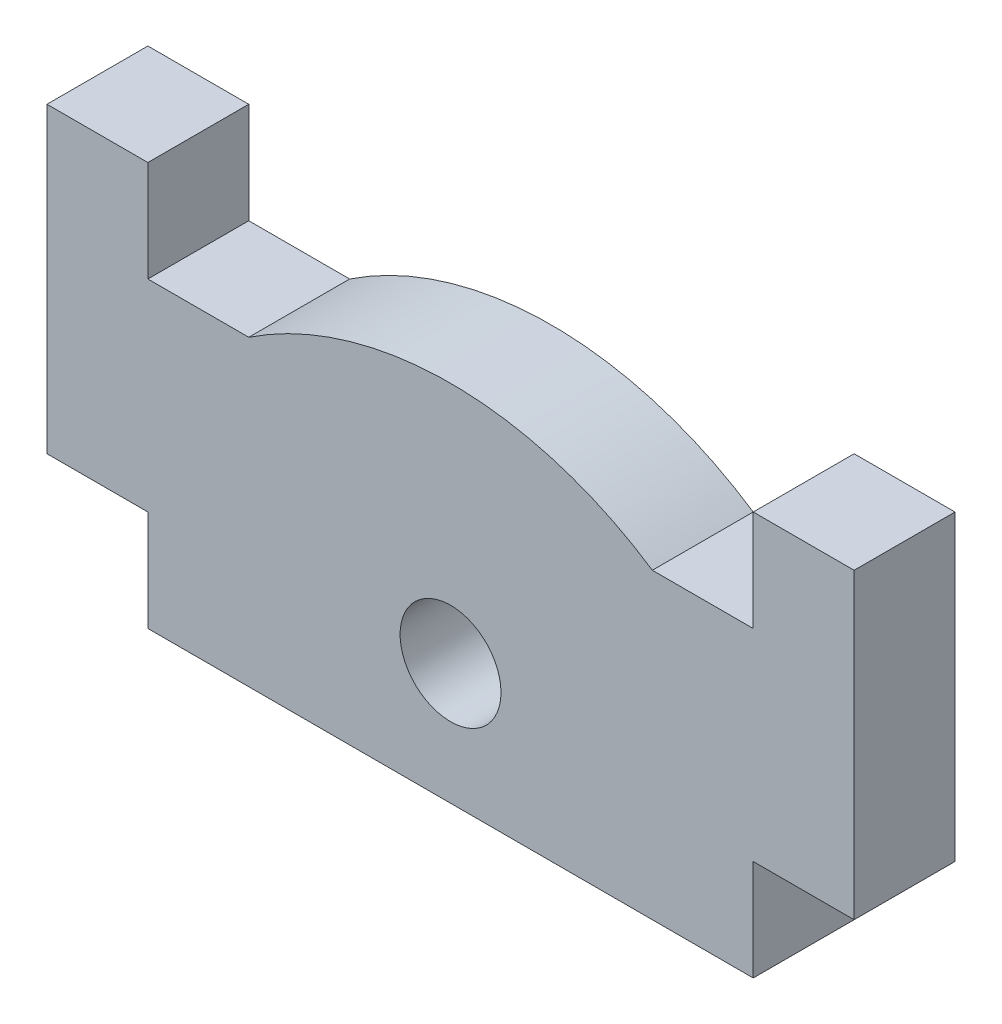
SolidWorks part; units mm, degrees
ref_plane "Front Plane" through (0, 0, 0) normal (0, 0, 1) x (1, 0, 0)
ref_plane "Top Plane" through (0, 0, 0) normal (0, 1, 0) x (1, 0, 0)
ref_plane "Right Plane" through (0, 0, 0) normal (1, 0, 0) x (0, 0, -1)
sketch "Sketch1" plane through (0, 0, 0) normal (0, 0, 1) x (1, 0, 0)
  line L0 (0, 0) -> (0, 14.5454) construction
  line L1 (0, 0) -> (18.3347, 0) construction
  line L2 (0, 6) -> (4, 6) construction
  line L3 (4, 6) -> (6, 6)
  line L4 (6, 6) -> (6, 8)
  line L5 (6, 8) -> (8, 8)
  line L6 (8, 8) -> (8, 2)
  line L7 (8, 2) -> (6, 2)
  line L8 (6, 2) -> (6, 0)
  line L9 (6, 0) -> (-6, 0)
  line L10 (-6, 2) -> (-6, 0)
  line L11 (-4, 6) -> (-6, 6)
  line L12 (-8, 2) -> (-6, 2)
  line L13 (-8, 8) -> (-8, 2)
  line L14 (-6, 8) -> (-8, 8)
  line L15 (-6, 6) -> (-6, 8)
  arc A0 (4, 6) -> (-4, 6) centre (0, 0) ccw
  circle A1 centre (0, 2.4) radius 1
  dimension "D7" = 2
  dimension "D1" = 6
  dimension "D2" = 2
  dimension "D3" = 2
  dimension "D4" = 6
  dimension "D5" = 6
  dimension "D6" = 6
  dimension "D8" = 2.4
  dimension "D9" = 2
extrude "Boss-Extrude1" add sketch "Sketch1" along normal blind 2
